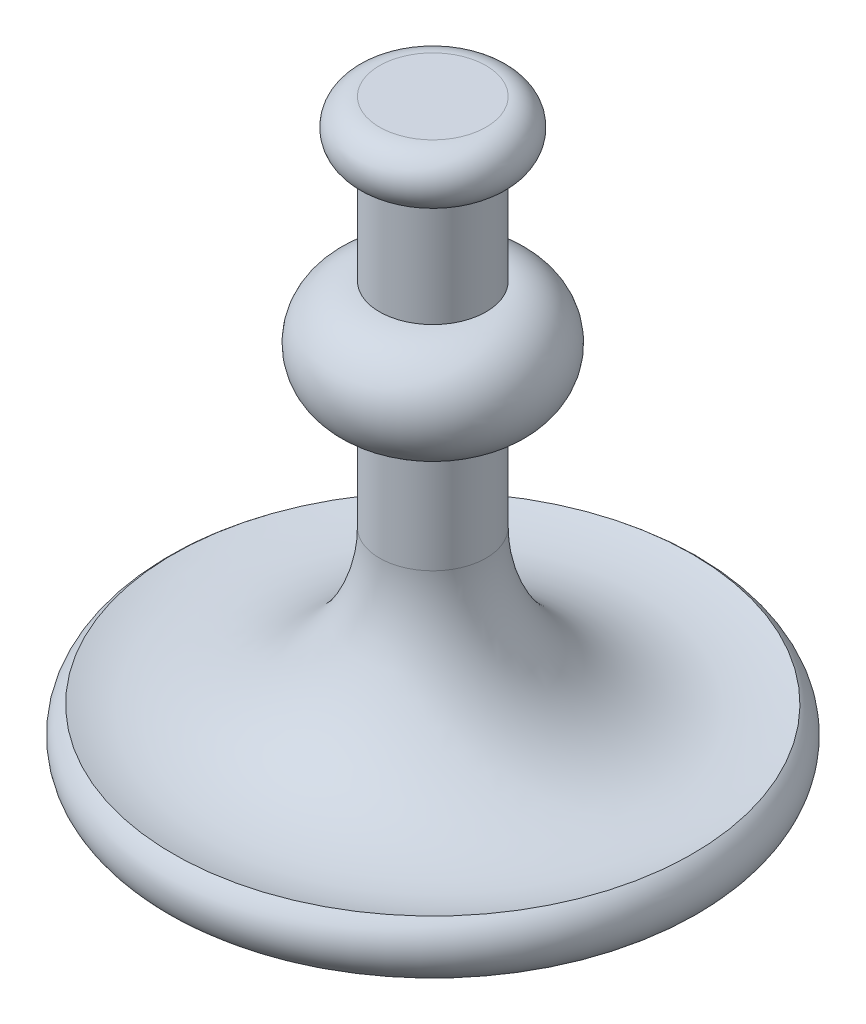
SolidWorks part; units mm, degrees
ref_plane "Front Plane" through (0, 0, 0) normal (0, 0, 1) x (1, 0, 0)
ref_plane "Top Plane" through (0, 0, 0) normal (0, 1, 0) x (1, 0, 0)
ref_plane "Right Plane" through (0, 0, 0) normal (1, 0, 0) x (0, 0, -1)
sketch "Sketch1" plane through (0, 0, 0) normal (0, 0, 1) x (1, 0, 0)
  line L0 (0, 0) -> (-90, 0)
  line L1 (-90, 0) -> (-90, 220)
  line L2 (-90, 220) -> (-70, 220)
  line L3 (-70, 200) -> (-70, 160)
  line L4 (-70, 120) -> (-70, 80)
  arc A0 (-70, 220) -> (-70, 200) centre (-70, 210) cw
  arc A1 (-70, 160) -> (-70, 120) centre (-70, 140) cw
  arc A4 (0, 0) -> (7.396, 22.5772) centre (0, 12.5) ccw
  arc A5 (-70, 80) -> (7.396, 22.5772) centre (-10, 80) ccw
  dimension "D4" = 10
  dimension "D6" = 20
  dimension "D7" = 12.5
  dimension "D9" = 80
  dimension "D8" = 60
  dimension "D1" = 90
  dimension "D2" = 220
  dimension "D3" = 20
  dimension "D5" = 40
revolve "Revolve1" add sketch "Sketch1" angle 360 about L1
